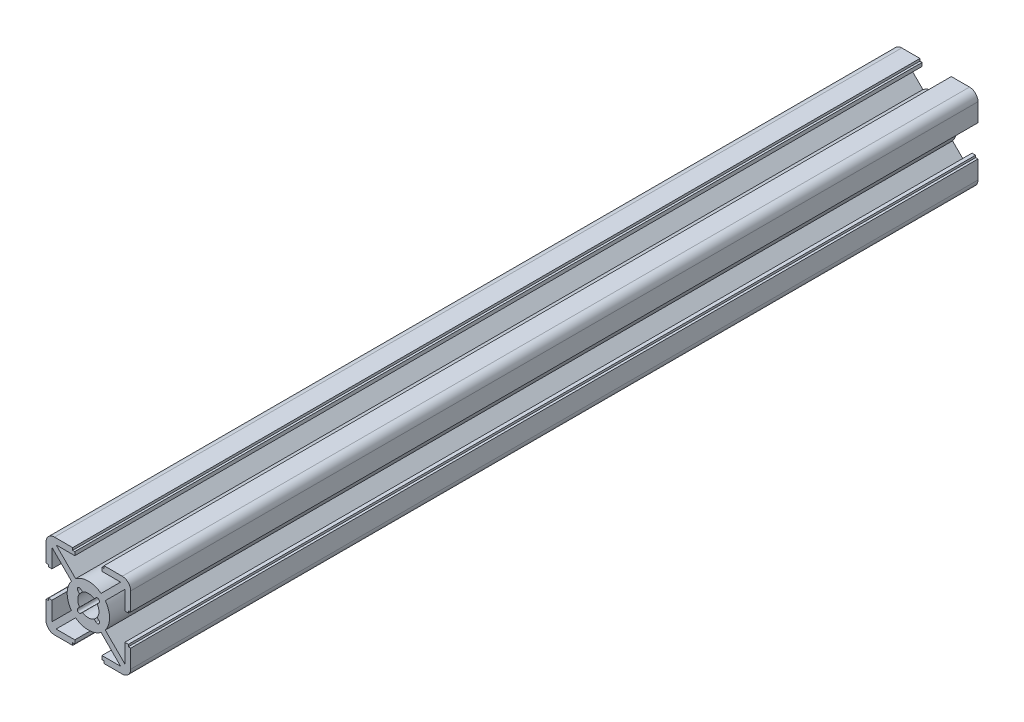
SolidWorks part; units mm, degrees
ref_plane "Ön Düzlem" through (0, 0, 0) normal (0, 0, 1) x (1, 0, 0)
ref_plane "Üst Düzlem" through (0, 0, 0) normal (0, 1, 0) x (1, 0, 0)
ref_plane "Sağ Düzlem" through (0, 0, 0) normal (1, 0, 0) x (0, 0, -1)
sketch "Çizim1" plane through (0, 0, 0) normal (0, 0, 1) x (1, 0, 0)
  line L0 (0, 13.544) -> (0, -12.4346) construction
  line L1 (0, 0) -> (-12.8733, -11.663) construction
  line L2 (15.4428, 0) -> (-17.1022, 0) construction
  line L3 (0, 0) -> (11.9441, 11.9441) construction
  line L4 (2.1213, 2.1213) -> (2.4749, 1.7678) construction
  line L5 (2.4749, 1.7678) -> (1.7678, 2.4749) construction
  line L6 (2.4749, 1.7678) -> (2.0856, 1.3785)
  line L7 (8.6, 7.6101) -> (8.6, 3.2)
  line L8 (1.3785, 2.0856) -> (1.7678, 2.4749)
  line L9 (8, 10) -> (3.7, 10)
  line L10 (3.7, 10) -> (3.7, 9.44)
  line L11 (3.7, 9.44) -> (3.2, 9.44)
  line L12 (3.2, 9.44) -> (3.2, 8.6)
  line L13 (3.0057, 3.9957) -> (7.6101, 8.6)
  line L14 (7.6101, 8.6) -> (3.2, 8.6)
  line L15 (9.44, 3.2) -> (8.6, 3.2)
  line L16 (9.44, 3.7) -> (9.44, 3.2)
  line L17 (10, 3.7) -> (9.44, 3.7)
  line L18 (10, 8) -> (10, 3.7)
  line L19 (8.6, 7.6101) -> (3.9957, 3.0057)
  line L20 (1.3785, -2.0856) -> (1.7678, -2.4749)
  line L21 (2.4749, -1.7678) -> (2.0856, -1.3785)
  line L22 (3.0057, -3.9957) -> (7.6101, -8.6)
  line L23 (3.2, -9.44) -> (3.2, -8.6)
  line L24 (3.7, -9.44) -> (3.2, -9.44)
  line L25 (3.7, -10) -> (3.7, -9.44)
  line L26 (7.6101, -8.6) -> (3.2, -8.6)
  line L27 (8, -10) -> (3.7, -10)
  line L28 (8.6, -7.6101) -> (3.9957, -3.0057)
  line L29 (8.6, -7.6101) -> (8.6, -3.2)
  line L30 (9.44, -3.2) -> (8.6, -3.2)
  line L31 (9.44, -3.7) -> (9.44, -3.2)
  line L32 (10, -3.7) -> (9.44, -3.7)
  line L33 (10, -8) -> (10, -3.7)
  line L34 (-1.3785, 2.0856) -> (-1.7678, 2.4749)
  line L35 (-2.4749, 1.7678) -> (-1.7678, 2.4749) construction
  line L36 (-2.1213, 2.1213) -> (-2.4749, 1.7678) construction
  line L37 (-10, -8) -> (-10, -3.7)
  line L38 (-10, -3.7) -> (-9.44, -3.7)
  line L39 (-9.44, -3.7) -> (-9.44, -3.2)
  line L40 (-9.44, -3.2) -> (-8.6, -3.2)
  line L41 (-8.6, -7.6101) -> (-8.6, -3.2)
  line L42 (-8.6, -7.6101) -> (-3.9957, -3.0057)
  line L43 (-8, -10) -> (-3.7, -10)
  line L44 (-7.6101, -8.6) -> (-3.2, -8.6)
  line L45 (-3.7, -10) -> (-3.7, -9.44)
  line L46 (-3.7, -9.44) -> (-3.2, -9.44)
  line L47 (-3.2, -9.44) -> (-3.2, -8.6)
  line L48 (-3.0057, -3.9957) -> (-7.6101, -8.6)
  line L49 (-2.4749, -1.7678) -> (-2.0856, -1.3785)
  line L50 (-1.3785, -2.0856) -> (-1.7678, -2.4749)
  line L51 (-8.6, 7.6101) -> (-3.9957, 3.0057)
  line L52 (-10, 8) -> (-10, 3.7)
  line L53 (-10, 3.7) -> (-9.44, 3.7)
  line L54 (-9.44, 3.7) -> (-9.44, 3.2)
  line L55 (-9.44, 3.2) -> (-8.6, 3.2)
  line L56 (-7.6101, 8.6) -> (-3.2, 8.6)
  line L57 (-3.0057, 3.9957) -> (-7.6101, 8.6)
  line L58 (-3.2, 9.44) -> (-3.2, 8.6)
  line L59 (-3.7, 9.44) -> (-3.2, 9.44)
  line L60 (-3.7, 10) -> (-3.7, 9.44)
  line L61 (-8, 10) -> (-3.7, 10)
  line L62 (-8.6, 7.6101) -> (-8.6, 3.2)
  line L63 (-2.4749, 1.7678) -> (-2.0856, 1.3785)
  arc A0 (1.3785, 2.0856) -> (-1.3785, 2.0856) centre (0, 0) ccw
  arc A1 (2.4749, 1.7678) -> (1.7678, 2.4749) centre (2.1213, 2.1213) ccw
  arc A2 (3.0057, 3.9957) -> (-3.0057, 3.9957) centre (0, 0) ccw
  arc A3 (3.9957, -3.0057) -> (3.9957, 3.0057) centre (0, 0) ccw
  arc A4 (2.0856, -1.3785) -> (2.0856, 1.3785) centre (0, 0) ccw
  arc A5 (1.3785, -2.0856) -> (-1.3785, -2.0856) centre (0, 0) cw
  arc A6 (2.4749, -1.7678) -> (1.7678, -2.4749) centre (2.1213, -2.1213) cw
  arc A7 (3.0057, -3.9957) -> (-3.0057, -3.9957) centre (0, 0) cw
  arc A8 (-2.4749, -1.7678) -> (-1.7678, -2.4749) centre (-2.1213, -2.1213) ccw
  arc A9 (-2.0856, -1.3785) -> (-2.0856, 1.3785) centre (0, 0) cw
  arc A10 (-3.9957, -3.0057) -> (-3.9957, 3.0057) centre (0, 0) cw
  arc A11 (-2.4749, 1.7678) -> (-1.7678, 2.4749) centre (-2.1213, 2.1213) cw
  arc A12 (-10, -8) -> (-8, -10) centre (-8, -8) ccw
  arc A13 (8, -10) -> (10, -8) centre (8, -8) ccw
  arc A14 (10, 8) -> (8, 10) centre (8, 8) ccw
  arc A15 (-10, 8) -> (-8, 10) centre (-8, 8) cw
  point P82 (-10, -10)
  point P85 (10, -10)
  point P88 (10, 10)
  point P91 (-10, 10)
  dimension "D1" = 5
  dimension "D3" = 1
  dimension "D6" = 10
  dimension "D8" = 2
  dimension "D2" = 45
  dimension "D4" = 0.5
  dimension "D5" = 3.2
  dimension "D7" = 0.7
  dimension "D10" = 1.4
  dimension "D12" = 0.84
extrude "Yükseklik-Ekstrüzyon1" add sketch "Çizim1" along normal blind 200
